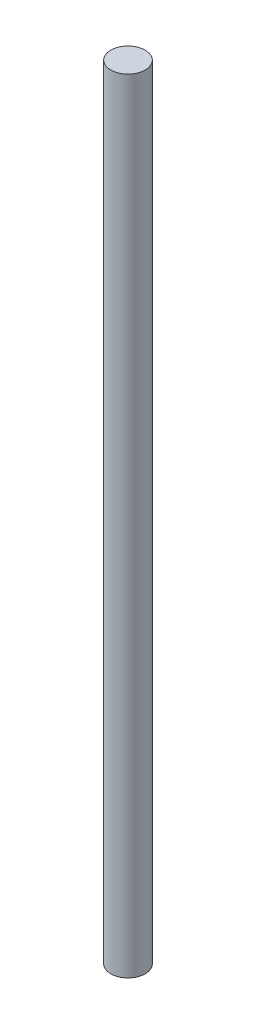
SolidWorks part; units mm, degrees
ref_plane "Front Plane" through (0, 0, 0) normal (0, 0, 1) x (1, 0, 0)
ref_plane "Top Plane" through (0, 0, 0) normal (0, 1, 0) x (1, 0, 0)
ref_plane "Right Plane" through (0, 0, 0) normal (1, 0, 0) x (0, 0, -1)
sketch "Sketch1" plane through (0, 0, 0) normal (0, 1, 0) x (1, 0, 0)
  circle A0 centre (-80.3559, 42.4547) radius 6.6
extrude "Boss-Extrude1" add sketch "Sketch1" along normal blind 300
